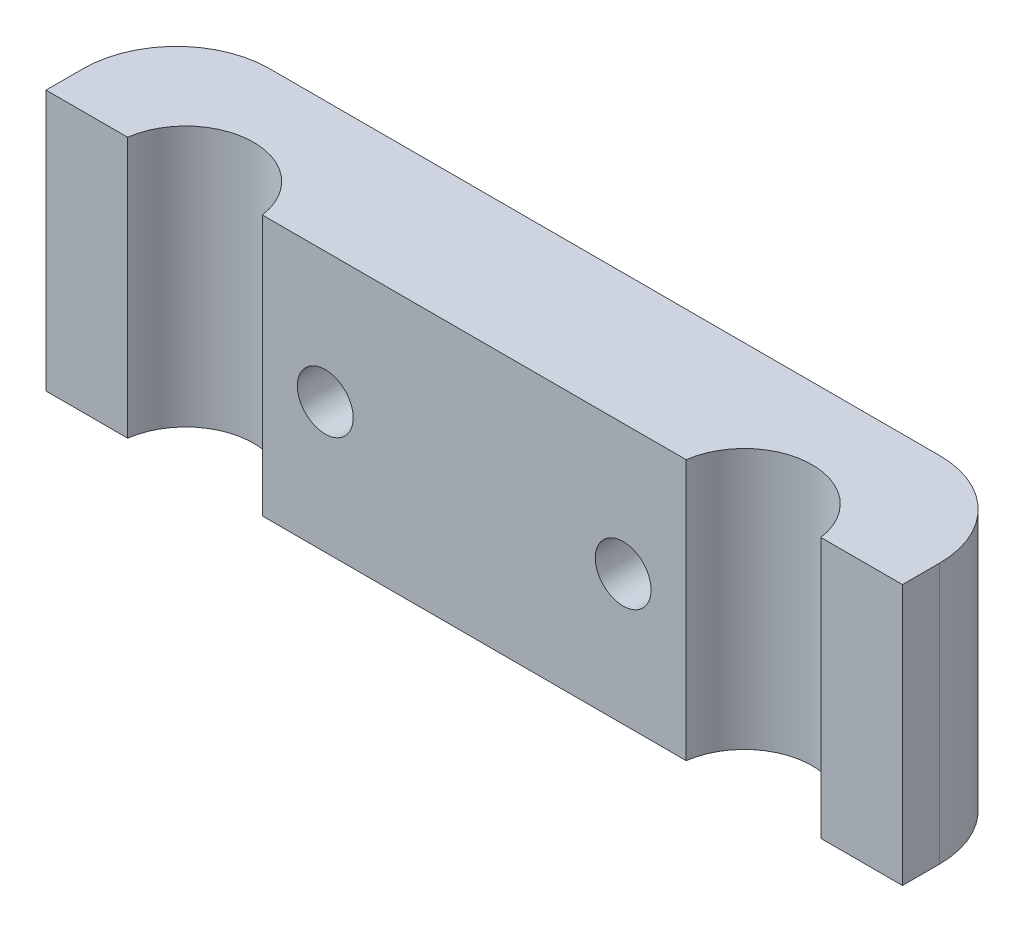
SolidWorks part; units mm, degrees
material "ABS"
ref_plane "Front" through (0, 0, 0) normal (0, 0, 1) x (1, 0, 0)
ref_plane "Top" through (0, 0, 0) normal (0, 1, 0) x (1, 0, 0)
ref_plane "Right" through (0, 0, 0) normal (1, 0, 0) x (0, 0, -1)
sketch "Эскиз1" plane through (0, 0, 0) normal (0, 0, 1) x (1, 0, 0)
  line L1 (-23, -7) -> (23, -7)
  line L2 (-23, -7) -> (-23, 7)
  line L3 (-23, 7) -> (23, 7)
  line L4 (23, -7) -> (23, 7)
  line L5 (-23, -7) -> (23, 7) construction
  line L6 (-23, 7) -> (23, -7) construction
  point P0 (0, 0)
  dimension "D1" = 46
  dimension "D2" = 14
extrude "Бобышка-Вытянуть1" add sketch "Эскиз1" along normal blind 7
sketch "Эскиз2" plane through (0, 0, 7) normal (0, 0, 1) x (1, 0, 0)
  line L0 (-23, 0) -> (23, 0) construction
  line L1 (-23, 7) -> (-23, -7) construction
  line L2 (23, -7) -> (23, 7) construction
  line L3 (0, 7) -> (0, 0) construction
  line L4 (23, 7) -> (-23, 7) construction
  circle A0 centre (-8, 0) radius 1.5
  circle A1 centre (8, 0) radius 1.5
  dimension "D1" = 8
extrude "Вырез-Вытянуть1" cut sketch "Эскиз2" against normal up to next
sketch "Эскиз3" plane through (0, 7, 0) normal (0, 1, 0) x (1, 0, 0)
  line L0 (0, 0) -> (0, -7) construction
  line L1 (23, 0) -> (-23, 0) construction
  line L2 (23, -7) -> (-23, -7) construction
  line L3 (0, -7.5) -> (-15, -7.5) construction
  circle A0 centre (-15, -7.5) radius 3.65
  circle A1 centre (15, -7.5) radius 3.65
  dimension "D2" = 7.3
  dimension "D3" = 7.5
  dimension "D1" = 15
extrude "Вырез-Вытянуть2" cut sketch "Эскиз3" against normal up to next
sketch "Эскиз4" plane through (0, 0, 0) normal (0, 0, -1) x (-1, 0, 0)
  circle A0 centre (-8, 0) radius 3
  circle A1 centre (8, 0) radius 3
extrude "Вырез-Вытянуть3" cut sketch "Эскиз4" against normal blind 3.8
fillet "Скругление1" radius 5 2 edges at (-23, 0, 0) (23, 0, 0)
